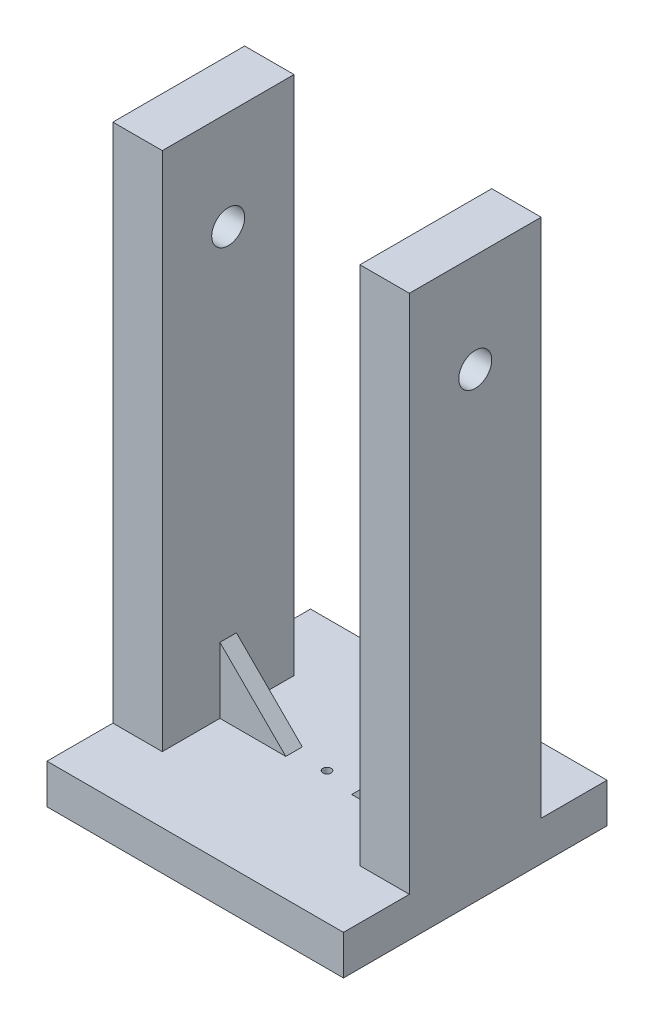
SolidWorks part; units mm, degrees
ref_plane "前视基准面" through (0, 0, 0) normal (0, 0, 1) x (1, 0, 0)
ref_plane "上视基准面" through (0, 0, 0) normal (0, 1, 0) x (1, 0, 0)
ref_plane "右视基准面" through (0, 0, 0) normal (1, 0, 0) x (0, 0, -1)
other "Configuration Table"
sketch "草图1" plane through (0, 0, 0) normal (0, 1, 0) x (1, 0, 0)
  line L1 (-45, 40) -> (45, 40)
  line L2 (-45, 40) -> (-45, -40)
  line L3 (-45, -40) -> (45, -40)
  line L4 (45, 40) -> (45, -40)
  line L5 (-45, 40) -> (45, -40) construction
  line L6 (-45, -40) -> (45, 40) construction
  point P0 (0, 0)
  dimension "D1" = 90
  dimension "D2" = 80
extrude "凸台-拉伸1" add sketch "草图1" along normal blind 12
sketch "草图2" plane through (0, 12, 0) normal (0, 1, 0) x (1, 0, 0)
  line L0 (-45, 40) -> (-45, -40) construction
  line L1 (-45, -20) -> (-30, -20)
  line L2 (-45, -20) -> (-45, 20)
  line L3 (-45, 20) -> (-30, 20)
  line L4 (-30, -20) -> (-30, 20)
  line L5 (-45, -20) -> (-30, 20) construction
  line L6 (-45, 20) -> (-30, -20) construction
  line L7 (45, -40) -> (45, 40) construction
  line L8 (30, -20) -> (45, -20)
  line L9 (30, -20) -> (30, 20)
  line L10 (30, 20) -> (45, 20)
  line L11 (45, -20) -> (45, 20)
  line L12 (30, -20) -> (45, 20) construction
  line L13 (30, 20) -> (45, -20) construction
  point P0 (-37.5, 0)
  point P7 (37.5, 0)
  point P15 (0, 0)
  point P16 (0, 0)
  dimension "D1" = 15
  dimension "D2" = 0
  dimension "D3" = 15
  dimension "D4" = 40
  dimension "D5" = 0
extrude "凸台-拉伸2" add sketch "草图2" along normal blind 158
sketch "草图3" plane through (0, 0, 0) normal (1, 0, 0) x (0, 0, -1)
  circle A0 centre (0, 140) radius 5
  dimension "D2" = 10
  dimension "D1" = 140
extrude "切除-拉伸1" cut sketch "草图3" against normal through all both and the other way through all
sketch "草图4" plane through (0, 12, 0) normal (0, 1, 0) x (1, 0, 0)
  circle A0 centre (0, 0) radius 1.25
  dimension "D1" = 2.5
extrude "切除-拉伸2" cut sketch "草图4" against normal blind 10 and the other way through all
sketch "草图6" plane through (0, 0, 0) normal (0, 0, 1) x (1, 0, 0)
  line L0 (-30, 32) -> (-10, 12)
  line L2 (-30, 170) -> (-30, 12) construction
  dimension "D1" = 20
  dimension "D2" = 0
  dimension "D3" = 20
rib "筋6" sketch "草图6" sketch "草图6" thickness 5 extrusion direction parallel to sketch draft on no parameters "D1"=5
mirror "镜向1" about plane through (0, 0, 0) normal (1, 0, 0) of "筋6"
